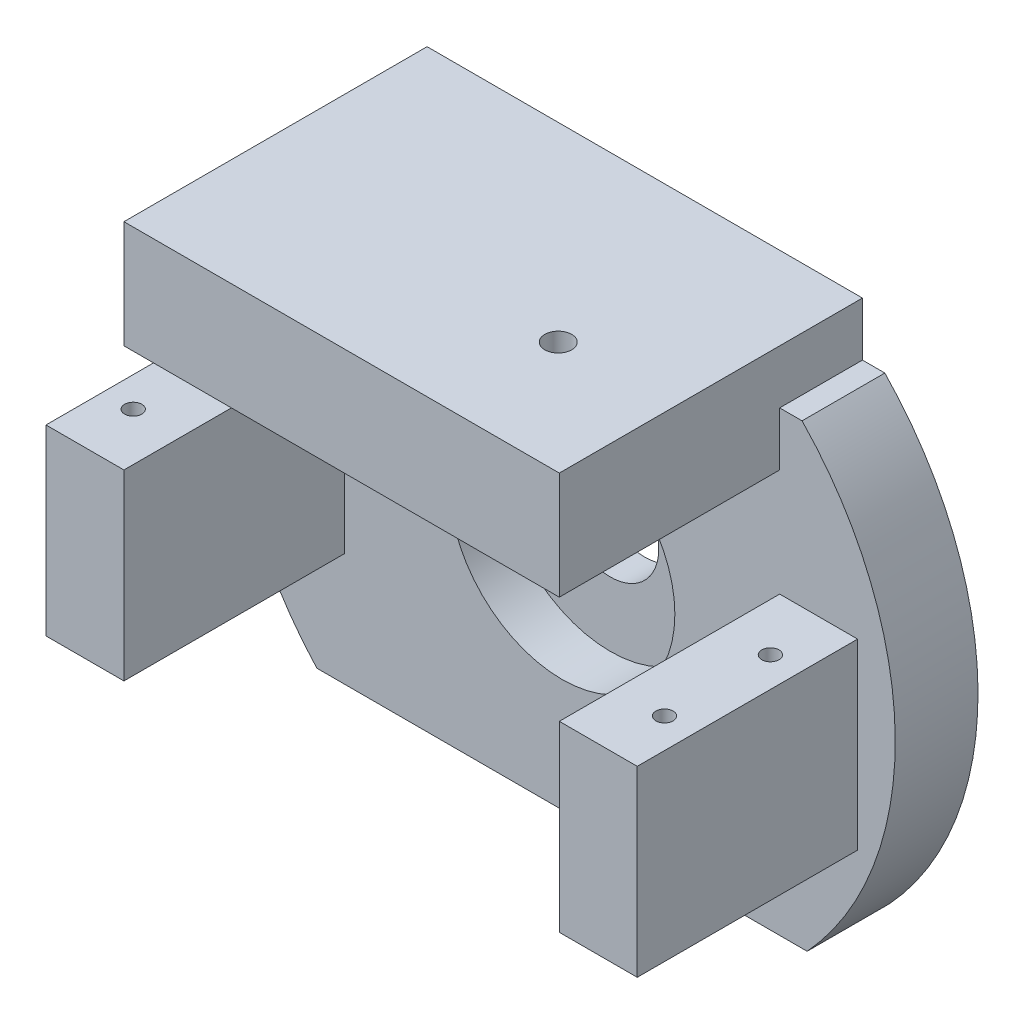
SolidWorks part; units mm, degrees
ref_plane "Plan de face" through (0, 0, 0) normal (0, 0, 1) x (1, 0, 0)
ref_plane "Plan de dessus" through (0, 0, 0) normal (0, 1, 0) x (1, 0, 0)
ref_plane "Plan de droite" through (0, 0, 0) normal (1, 0, 0) x (0, 0, -1)
sketch "Esquisse1" plane through (0, 0, 0) normal (0, 0, 1) x (1, 0, 0)
  line L1 (-27.5, 21.5) -> (27.5, 21.5)
  line L2 (-27.5, 21.5) -> (-27.5, -21.5)
  line L3 (-27.5, -21.5) -> (27.5, -21.5)
  line L4 (27.5, 21.5) -> (27.5, -21.5)
  line L5 (-27.5, 21.5) -> (27.5, -21.5) construction
  line L6 (-27.5, -21.5) -> (27.5, 21.5) construction
  point P0 (0, 0)
  dimension "D1" = 55
  dimension "D2" = 43
extrude "Boss.-Extru.1" add sketch "Esquisse1" along normal blind 27
sketch "Esquisse2" plane through (0, -21.5, 0) normal (0, -1, 0) x (1, 0, 0)
  line L0 (27.5, 27) -> (27.5, 0) construction
  line L1 (-27.5, 0) -> (27.5, 0) construction
  line L2 (-27.5, 0) -> (-27.5, 6.5) construction
  line L3 (-27.5, 6.5) -> (27.5, 6.5) construction
  line L4 (27.5, 0) -> (27.5, 6.5) construction
  line L5 (0, 0) -> (0, 33.905) construction
  line L6 (-20.25, 6.5) -> (20.25, 6.5)
  line L7 (-20.25, 6.5) -> (-20.25, 28.1766)
  line L8 (-20.25, 28.1766) -> (20.25, 28.1766)
  line L9 (20.25, 6.5) -> (20.25, 28.1766)
  dimension "D1" = 6.5
  dimension "D2" = 40.5
extrude "Enlèv. mat.-Extru.1" cut sketch "Esquisse2" against normal offset from surface (38 mm away) 5 up to face at (0, 21.5, 13.5)
sketch "Esquisse3" plane through (0, -21.5, 0) normal (0, -1, 0) x (1, 0, 0)
  line L0 (-20.25, 16.75) -> (28.5647, 16.75) construction
  line L1 (-20.25, 6.5) -> (-20.25, 27) construction
  line L2 (0, 27) -> (0, -2.6321) construction
  line L3 (-20.25, 27) -> (20.25, 27) construction
  line L4 (-20.25, 27) -> (-20.25, 6.5) construction
  circle A0 centre (-24.71, 21.675) radius 0.7
  circle A2 centre (-24.71, 11.825) radius 0.7
  circle A3 centre (24.71, 11.825) radius 0.7
  circle A4 centre (24.71, 21.675) radius 0.7
  point P9 (-24.71, 21.675)
  point P12 (-24.71, 11.825)
  point P13 (24.71, 11.825)
  point P14 (24.71, 21.675)
  dimension "D4" = 1.4
  dimension "D1" = 4.46
  dimension "D2" = 4.925
  dimension "D3" = 9.85
extrude "Enlèv. mat.-Extru.2" cut sketch "Esquisse3" against normal up to surface (43 mm away) up to face at (0, 21.5, 13.5)
sketch "Esquisse4" plane through (0, -21.5, 0) normal (0, -1, 0) x (1, 0, 0)
  line L0 (27.5, 27) -> (27.5, 0) construction
  line L1 (-27.5, 27) -> (27.5, 27)
  line L2 (-27.5, 27) -> (-27.5, 6.5)
  line L3 (-27.5, 6.5) -> (27.5, 6.5)
  line L4 (27.5, 27) -> (27.5, 6.5)
extrude "Enlèv. mat.-Extru.3" cut sketch "Esquisse4" against normal offset from surface (11 mm away) 27 up to face at (0, 16.5, 16.75)
sketch "Esquisse5" plane through (-27.5, 0, 0) normal (-1, 0, 0) x (0, 0, 1)
  line L6 (6.5, 16.5) -> (27, 16.5)
  line L7 (6.5, 16.5) -> (6.5, 6.5)
  line L8 (6.5, 6.5) -> (27, 6.5)
  line L9 (27, 16.5) -> (27, 6.5)
  line L10 (27, 21.5) -> (27, -10.5) construction
  line L11 (27, 21.5) -> (0, 21.5) construction
  line L13 (6.5, -10.5) -> (6.5, -21.5) construction
  dimension "D1" = 5
  dimension "D2" = 10
extrude "Enlèv. mat.-Extru.6" cut sketch "Esquisse5" against normal up to surface (55 mm away) up to face at (27.5, -3.5, 11.1667)
sketch "Esquisse6" plane through (0, 16.5, 0) normal (0, -1, 0) x (1, 0, 0)
  line L1 (-27.5, 27) -> (-20.25, 27)
  line L2 (-27.5, 27) -> (-27.5, 6.5)
  line L3 (-27.5, 6.5) -> (-20.25, 6.5)
  line L4 (-20.25, 27) -> (-20.25, 6.5)
  line L5 (20.25, 27) -> (27.5, 27)
  line L6 (20.25, 27) -> (20.25, 6.5)
  line L7 (20.25, 6.5) -> (27.5, 6.5)
  line L8 (27.5, 27) -> (27.5, 6.5)
extrude "Enlèv. mat.-Extru.7" cut sketch "Esquisse6" against normal up to surface (5 mm away) up to face at (24.71, 21.5, 20.975)
sketch "Esquisse7" plane through (0, 0, 0) normal (0, 0, -1) x (-1, 0, 0)
  circle A0 centre (0, 0) radius 31
  dimension "D1" = 62
extrude "Boss.-Extru.2" add sketch "Esquisse7" against normal up to surface (6.5 mm away) up to face at (0, 3.75, 6.5)
sketch "Esquisse8" plane through (0, 0, 0) normal (0, 0, -1) x (-1, 0, 0)
  circle A0 centre (0, 0) radius 31
  circle A1 centre (0, 0) radius 41
  arc A2 (22.3327, 21.5) -> (-22.3327, 21.5) centre (0, 0) ccw construction
  dimension "D1" = 62
  dimension "D2" = 82
extrude "Enlèv. mat.-Extru.8" cut sketch "Esquisse8" against normal up to surface (6.5 mm away) up to face at (0, 0, 6.5)
hole_wizard "Trou taraudé M2x0.41" positions "Esquisse3D1" profile "Esquisse9" tap size "M2x0.4" standard "Ansi Metric" end condition through all
sketch3d "Esquisse3D1"
  line L0 (-24.71, 6.5, 21.675) -> (-24.71, -10.5, 21.675) construction
  line L1 (-24.71, 6.5, 11.825) -> (-24.71, -10.5, 11.825) construction
  line L2 (24.71, 6.5, 21.675) -> (24.71, -10.5, 21.675) construction
  line L3 (24.71, 6.5, 11.825) -> (24.71, -10.5, 11.825) construction
  point P0 (-24.71, -10.5, 21.675)
  point P4 (-24.71, -10.5, 11.825)
  point P8 (24.71, -10.5, 21.675)
  point P12 (24.71, -10.5, 11.825)
sketch "Esquisse9" plane through (-24.71, -10.5, 21.675) normal (1, 0, 0) x (0, 0, -1)
  line L0 (0, 0) -> (0, 41.5)
  line L1 (0, 41.5) -> (0.8, 41.5)
  line L2 (0.8, 41.5) -> (0.8, 0)
  line L5 (0.8, 0) -> (0, 0)
  line L11 (0, -6.35) -> (0, 107.95) construction
  dimension "Diamètre du trou pour taraudage jusqu'au prochain" = 1.6
  dimension "Profondeur du trou pour taraudage jusqu'au prochain" = 41.5
cosmetic thread "Filetage de perçage1" parameters "D2"=2
cosmetic thread "Filetage de perçage2" parameters "D2"=2
cosmetic thread "Filetage de perçage3" parameters "D2"=2
cosmetic thread "Filetage de perçage4" parameters "D2"=2
sketch "Esquisse10" plane through (0, 0, 6.5) normal (0, 0, 1) x (1, 0, 0)
  circle A0 centre (0, 0) radius 10.5
  dimension "D1" = 21
extrude "Enlèv. mat.-Extru.9" cut sketch "Esquisse10" against normal offset from surface (4.5 mm away) 2 up to face at (-31, 0, 0)
sketch "Esquisse11" plane through (0, 0, 2) normal (0, 0, 1) x (1, 0, 0)
  circle A0 centre (0, 0) radius 4.5
  dimension "D1" = 9
extrude "Enlèv. mat.-Extru.10" cut sketch "Esquisse11" against normal up to surface (2 mm away) up to face at (-31, 0, 0)
sketch "Esquisse12" plane through (0, 21.5, 0) normal (0, 1, 0) x (1, 0, 0)
  line L0 (0, 0) -> (0, -31.7536) construction
  circle A0 centre (0, -15.8768) radius 9.25
  circle A1 centre (0, -15.8768) radius 1.25
  dimension "D1" = 18.5
  dimension "D2" = 2.5
extrude "Boss.-Extru.3" add sketch "Esquisse12" along normal blind 5
sketch "Esquisse13" plane through (0, 0, 6.5) normal (0, 0, 1) x (1, 0, 0)
  line L0 (-26.0408, 21.5) -> (24.0741, 21.5)
  line L1 (24.0741, 21.5) -> (24.0741, 33.5126)
  line L2 (24.0741, 33.5126) -> (-26.0408, 33.5126)
  line L3 (-26.0408, 33.5126) -> (-26.0408, 21.5)
extrude "Enlèv. mat.-Extru.11" cut sketch "Esquisse13" against normal up to surface (6.5 mm away) up to face at (4.5, 0, 0)
sketch "Esquisse14" plane through (0, 0, 0) normal (0, 0, -1) x (-1, 0, 0)
  line L0 (-22.3327, 21.5) -> (22.3327, 21.5) construction
  line L1 (-22.3327, 21.5) -> (22.3327, 21.5)
  arc A0 (-22.3327, 21.5) -> (22.3327, 21.5) centre (0, 0) ccw construction
  arc A1 (-22.3327, 21.5) -> (22.3327, 21.5) centre (0, 0) ccw
extrude "Boss.-Extru.4" add sketch "Esquisse14" along normal blind 1.2
sketch "Esquisse15" plane through (0, 0, 6.5) normal (0, 0, 1) x (1, 0, 0)
  line L0 (0, 0) -> (0, -35.7271) construction
  line L1 (26.5027, -31) -> (-26.5027, -31)
  line L2 (26.5027, -31) -> (26.5027, -21)
  line L3 (26.5027, -21) -> (-26.5027, -21)
  line L4 (-26.5027, -31) -> (-26.5027, -21)
  arc A0 (-22.3327, 21.5) -> (22.3327, 21.5) centre (0, 0) ccw construction
  dimension "D1" = 10
extrude "Enlèv. mat.-Extru.12" cut sketch "Esquisse15" against normal up to surface (7.7 mm away) up to face at (0, -4.75, -1.2)
sketch "Esquisse16" plane through (0, 0, 0) normal (0, 0, 1) x (1, 0, 0)
  circle A0 centre (0, 0) radius 4.5
extrude "Enlèv. mat.-Extru.13" cut sketch "Esquisse16" against normal up to surface (1.2 mm away) up to face at (0, 0.2967, -1.2)
sketch "Esquisse17" plane through (0, 0, 27) normal (0, 0, 1) x (1, 0, 0)
  line L0 (-20.25, 16.5) -> (20.25, 16.5) construction
  line L1 (-20.25, 21.5) -> (20.25, 21.5)
  line L2 (-20.25, 21.5) -> (-20.25, 26.5)
  line L3 (-20.25, 26.5) -> (20.25, 26.5)
  line L4 (20.25, 21.5) -> (20.25, 26.5)
  dimension "D1" = 10
extrude "Boss.-Extru.5" add sketch "Esquisse17" against normal up to vertex (42.9105 mm away)
sketch "Esquisse18" plane through (0, 26.5, 0) normal (0, 1, 0) x (1, 0, 0)
  line L0 (0, 1.2) -> (0, -28.8976) construction
  line L1 (20.25, 1.2) -> (-20.25, 1.2) construction
  line L2 (-20.25, -16.5) -> (30.3033, -16.5) construction
  line L5 (-20.25, -6.5) -> (-20.25, -27) construction
  line L6 (-20.25, -6.5) -> (-27.5, -6.5) construction
  circle A0 centre (9.65, -16.5) radius 9.25 construction
  circle A1 centre (9.65, -16.5) radius 1
  point P12 (0, -12.9)
  dimension "D1" = 29.9
  dimension "D2" = 10
extrude "Enlèv. mat.-Extru.14" cut sketch "Esquisse18" against normal up to surface (10 mm away) up to face at (0, 16.5, 16.75)
hole_wizard "Trou taraudé M3x0.51" positions "Esquisse3D2" profile "Esquisse19" tap size "M3x0.5" standard "Ansi Metric" end condition through all
sketch3d "Esquisse3D2"
  line L0 (9.65, 16.5, 16.5) -> (9.65, 26.5, 16.5) construction
  point P0 (9.65, 26.5, 16.5)
sketch "Esquisse19" plane through (9.65, 26.5, 16.5) normal (1, 0, 0) x (0, 0, 1)
  line L0 (0, 0) -> (0, 47.5)
  line L1 (0, 47.5) -> (1.25, 47.5)
  line L2 (1.25, 47.5) -> (1.25, 0)
  line L5 (1.25, 0) -> (0, 0)
  line L11 (0, -6.35) -> (0, 107.95) construction
  dimension "Diamètre du trou pour taraudage jusqu'au prochain" = 2.5
  dimension "Profondeur du trou pour taraudage jusqu'au prochain" = 47.5
cosmetic thread "Filetage de perçage5" parameters "D2"=3
equation "\"1c\"=0.00309185"
equation "\"D2@Esquisse8\"=\"D1@Esquisse8\"+2cm"
